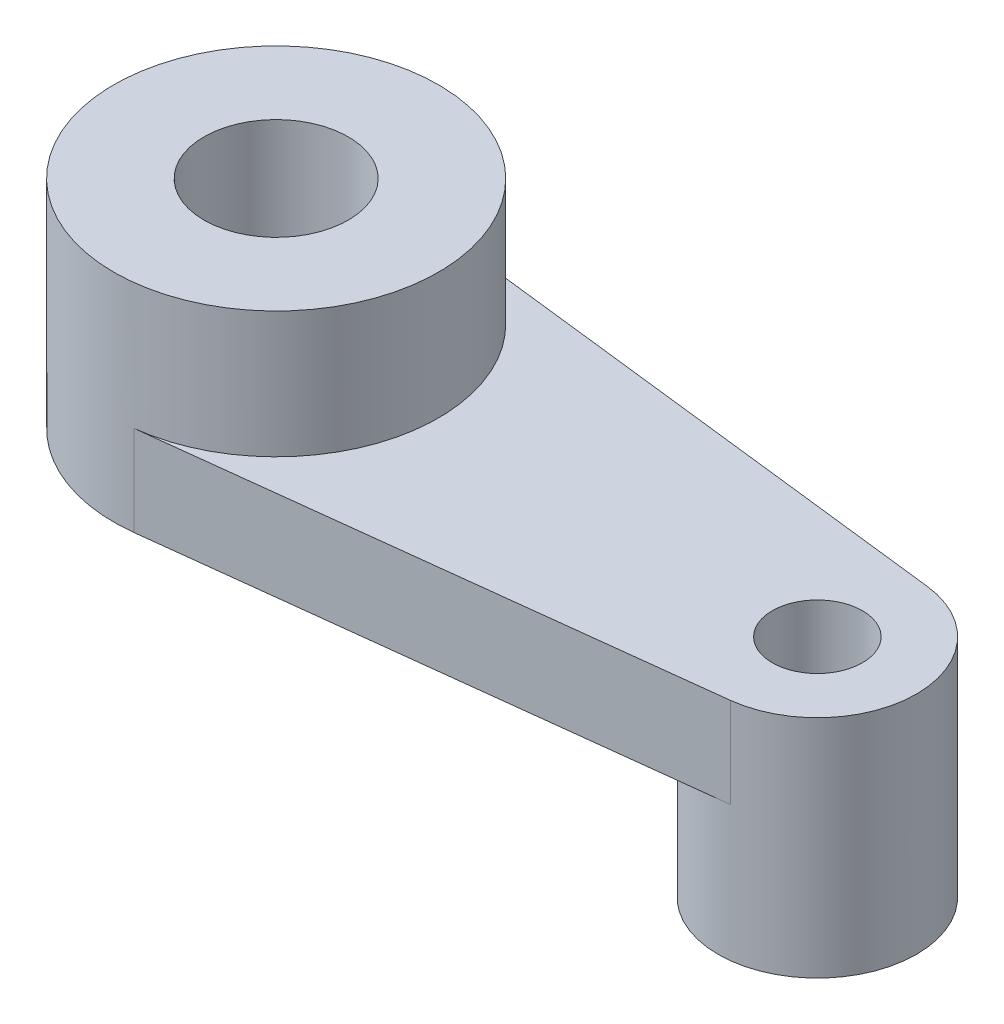
SolidWorks part; units mm, degrees
ref_plane "前视基准面" through (0, 0, 0) normal (0, 0, 1) x (1, 0, 0)
ref_plane "上视基准面" through (0, 0, 0) normal (0, 1, 0) x (1, 0, 0)
ref_plane "右视基准面" through (0, 0, 0) normal (1, 0, 0) x (0, 0, -1)
sketch "草图1" plane through (0, 0, 0) normal (0, 1, 0) x (1, 0, 0)
  circle A0 centre (0, 0) radius 18
extrude "凸台-拉伸1" add sketch "草图1" along normal blind 24
sketch "草图2" plane through (0, 0, 0) normal (0, 1, 0) x (1, 0, 0)
  line L0 (2.1, 17.8771) -> (61.2833, 10.9249)
  line L1 (61.2833, -10.9249) -> (2.1, -17.8771)
  arc A0 (61.2833, 10.9249) -> (61.2833, -10.9249) centre (60, 0) cw
  arc A1 (2.1, -17.8771) -> (2.1, 17.8771) centre (0, 0) cw
extrude "凸台-拉伸2" add sketch "草图2" along normal blind 10
sketch "草图3" plane through (0, 0, 0) normal (0, 1, 0) x (1, 0, 0)
  circle A0 centre (60, 0) radius 11
extrude "凸台-拉伸3" add sketch "草图3" against normal blind 15
ref_plane "基准面1" through (0, 24, 0) normal (0, 1, 0) x (1, 0, 0)
sketch "草图4" plane through (0, 24, 0) normal (0, 1, 0) x (1, 0, 0)
  circle A0 centre (0, 0) radius 8
extrude "切除-拉伸1" cut sketch "草图4" against normal through all
ref_plane "基准面2" through (0, -15, 0) normal (0, 1, 0) x (1, 0, 0)
sketch "草图5" plane through (0, -15, 0) normal (0, 1, 0) x (1, 0, 0)
  circle A0 centre (60, 0) radius 5
extrude "切除-拉伸2" cut sketch "草图5" along normal through all
